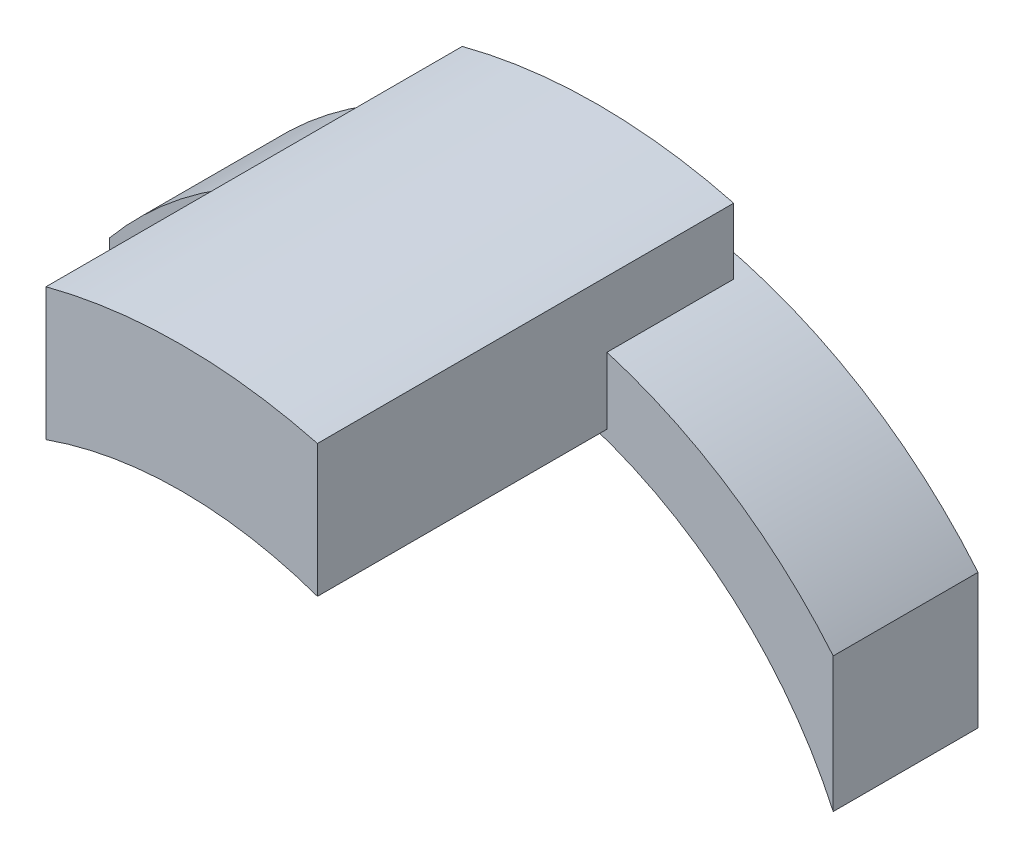
SolidWorks part; units mm, degrees
ref_plane "Front Plane" through (0, 0, 0) normal (0, 0, 1) x (1, 0, 0)
ref_plane "Top Plane" through (0, 0, 0) normal (0, 1, 0) x (1, 0, 0)
ref_plane "Right Plane" through (0, 0, 0) normal (1, 0, 0) x (0, 0, -1)
sketch "Sketch1" plane through (0, 0, 0) normal (0, 0, 1) x (1, 0, 0)
  line L0 (-20, 9.1652) -> (-20, 16.6132)
  line L1 (20, 16.6132) -> (20, 9.1652)
  arc A0 (20, 9.1652) -> (-20, 9.1652) centre (0, 0) ccw
  arc A1 (20, 16.6132) -> (-20, 16.6132) centre (0, 0) ccw
  dimension "D1" = 44
  dimension "D3" = 4
  dimension "D2" = 40
extrude "Extrude1" add sketch "Sketch1" along normal mid plane 8
sketch "Sketch2" plane through (0, 0, 4) normal (0, 0, -1) x (-1, 0, 0)
  line L0 (7.5, 21.2132) -> (7.5, 28.5307)
  line L1 (-7.5, 28.5307) -> (-7.5, 21.2132)
  arc A0 (7.5, 28.5307) -> (-7.5, 28.5307) centre (0, 0) ccw
  arc A2 (7.5, 21.2132) -> (-7.5, 21.2132) centre (0, 0) ccw
  arc A3 (20, 9.1652) -> (-20, 9.1652) centre (0, 0) ccw construction
  dimension "D2" = 7
  dimension "D3" = 0.5
  dimension "D1" = 15
extrude "Extrude2" add sketch "Sketch2" against normal blind 16 and the other way blind 7
